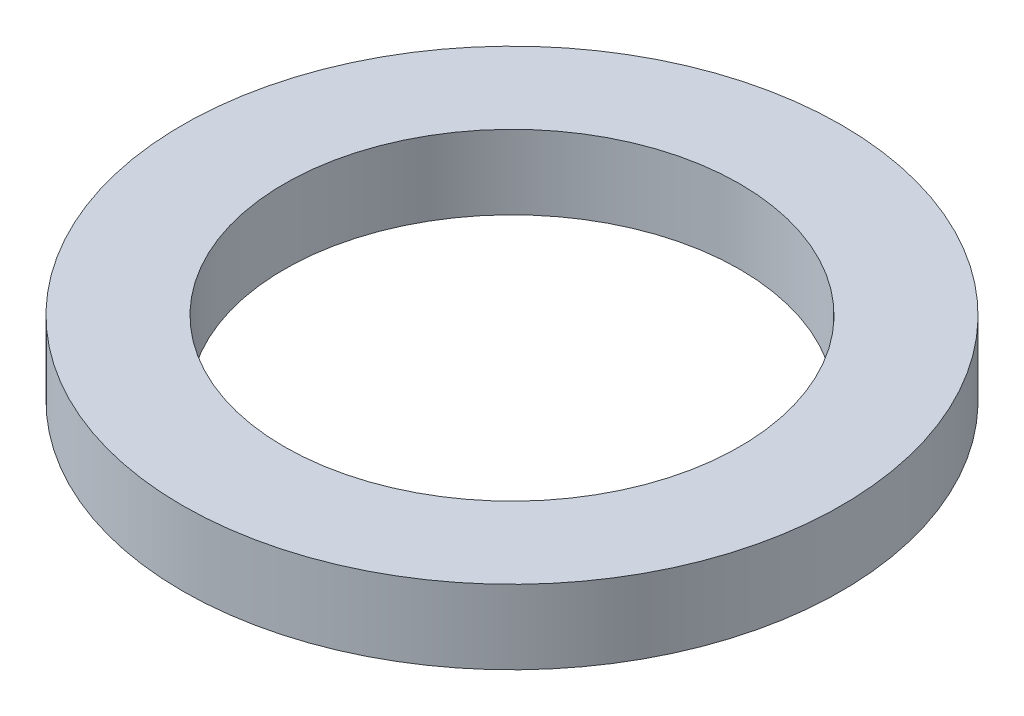
SolidWorks part; units mm, degrees
ref_plane "Front Plane" through (0, 0, 0) normal (0, 0, 1) x (1, 0, 0)
ref_plane "Top Plane" through (0, 0, 0) normal (0, 1, 0) x (1, 0, 0)
ref_plane "Right Plane" through (0, 0, 0) normal (1, 0, 0) x (0, 0, -1)
sketch "Sketch1" plane through (0, 0, 0) normal (0, 1, 0) x (1, 0, 0)
  circle A0 centre (0, 0) radius 2.2606
  dimension "OD" = 4.5212
extrude "Boss-Extrude1" add sketch "Sketch1" along normal blind 0.508
sketch "Sketch5" plane through (0, 0.508, 0) normal (0, 1, 0) x (-1, 0, 0)
  circle A0 centre (0, 0) radius 1.5621
  dimension "ID" = 3.1242
extrude "Cut-Extrude1" cut sketch "Sketch5" against normal through all
